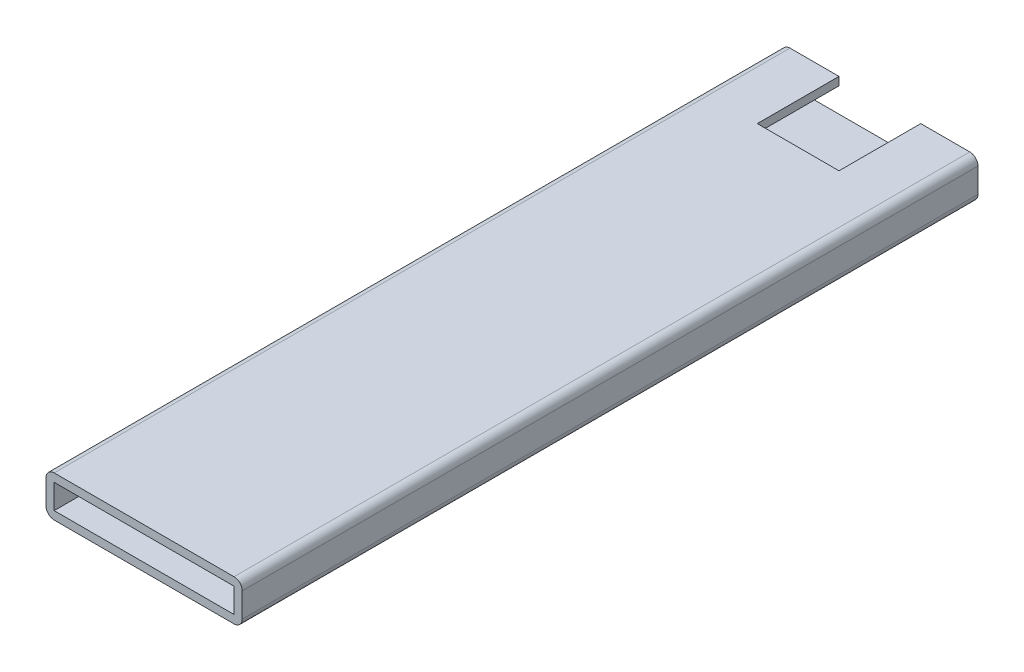
SolidWorks part; units mm, degrees
ref_plane "前视基准面" through (0, 0, 0) normal (0, 0, 1) x (1, 0, 0)
ref_plane "上视基准面" through (0, 0, 0) normal (0, 1, 0) x (1, 0, 0)
ref_plane "右视基准面" through (0, 0, 0) normal (1, 0, 0) x (0, 0, -1)
other "Configuration Table"
sketch "草图1" plane through (0, 0, 0) normal (0, 0, 1) x (1, 0, 0)
  line L1 (0, 0) -> (22, 0)
  line L2 (0, 0) -> (0, 3)
  line L3 (0, 3) -> (22, 3)
  line L4 (22, 0) -> (22, 3)
  line L5 (0, 4) -> (22, 4)
  line L6 (-1, 3) -> (-1, 0)
  line L7 (0, -1) -> (22, -1)
  line L8 (23, 3) -> (23, 0)
  arc A0 (22, -1) -> (23, 0) centre (22, 0) ccw
  arc A1 (22, 4) -> (23, 3) centre (22, 3) cw
  arc A2 (-1, 0) -> (0, -1) centre (0, 0) ccw
  arc A3 (0, 4) -> (-1, 3) centre (0, 3) ccw
  dimension "D7" = 1
  dimension "D1" = 22
  dimension "D2" = 3
  dimension "D3" = 1
  dimension "D4" = 1
  dimension "D5" = 1
  dimension "D6" = 1
extrude "凸台-拉伸1" add sketch "草图1" along normal blind 90
sketch "草图2" plane through (0, 4, 0) normal (0, 1, 0) x (1, 0, 0)
  line L0 (22, 0) -> (0, 0) construction
  line L1 (6, 0) -> (6, -10)
  line L2 (6, -10) -> (16, -10)
  line L3 (16, -10) -> (16, 0)
  line L4 (6, 0) -> (16, 0)
  point P0 (6, 0)
  point P1 (16, 0)
  dimension "D1" = 6
  dimension "D2" = 10
  dimension "D3" = 10
extrude "切除-拉伸1" cut sketch "草图2" against normal blind 1
